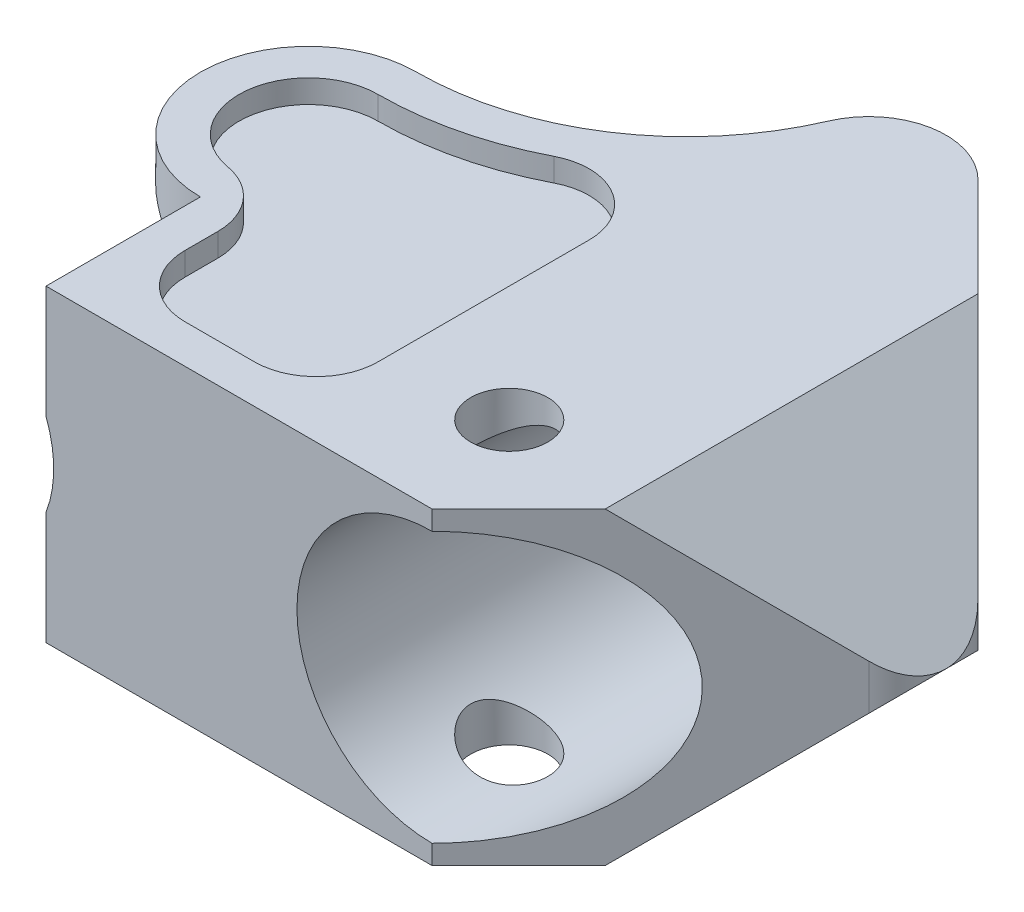
SolidWorks part; units mm, degrees
material "Alliage 1060"
ref_plane "Plan de face" through (0, 0, 0) normal (0, 0, 1) x (1, 0, 0)
ref_plane "Plan de dessus" through (0, 0, 0) normal (0, 1, 0) x (1, 0, 0)
ref_plane "Plan de droite" through (0, 0, 0) normal (1, 0, 0) x (0, 0, -1)
sketch "Esquisse1" plane through (0, 0, 0) normal (0, 1, 0) x (1, 0, 0)
  line L0 (0, 0) -> (50, 0)
  line L1 (50, 0) -> (78.2843, 28.2843)
  line L2 (0, 0) -> (0, 20)
  line L3 (78.2843, 42.4264) -> (48.4126, 72.2981)
  arc A0 (0, 20) -> (0, 48) centre (0, 34) cw
  arc A1 (0, 48) -> (32.1545, 69.1766) centre (0, 83) ccw
  arc A2 (78.2843, 28.2843) -> (78.2843, 42.4264) centre (71.2132, 35.3553) ccw
  arc A3 (48.4126, 72.2981) -> (32.1545, 69.1766) centre (41.3415, 65.227) ccw
  point P17 (85.3553, 35.3553)
  dimension "D5" = 14
  dimension "D7" = 70
  dimension "D8" = 10
  dimension "D3" = 135
  dimension "D4" = 20
  dimension "D6" = 90
  dimension "D1" = 50
  dimension "D2" = 50
extrude "Boss.-Extru.1" add sketch "Esquisse1" along normal mid plane 40
sketch "Esquisse2" plane through (0, 20, 0) normal (0, 1, 0) x (1, 0, 0)
  line L6 (30, 20) -> (30, 0)
  line L8 (30, 40.3385) -> (30, 13)
  line L9 (5, 26.5167) -> (5, 5)
  line L10 (5, 5) -> (47.9289, 5)
  line L11 (47.9289, 5) -> (74.7487, 31.8198)
  line L14 (74.7487, 38.8909) -> (44.8771, 68.7626)
  line L15 (5, 17.2668) -> (5, 13)
  line L16 (13, 5) -> (22, 5)
  arc A8 (5, 17.2668) -> (-1.5882, 25.1412) centre (-3, 17.2668) ccw
  arc A9 (5, 13) -> (13, 5) centre (13, 13) ccw
  arc A10 (22, 5) -> (30, 13) centre (22, 13) ccw
  arc A11 (30, 40.3385) -> (18.3333, 47.4488) centre (22, 40.3385) ccw
  arc A16 (74.7487, 31.8198) -> (74.7487, 38.8909) centre (71.2132, 35.3553) ccw
  arc A17 (44.8771, 68.7626) -> (36.748, 67.2018) centre (41.3415, 65.227) ccw
  arc A18 (0, 43) -> (36.748, 67.2018) centre (0, 83) ccw
  arc A19 (0, 43) -> (5, 26.5167) centre (0, 34) ccw
  arc A22 (0, 43) -> (18.3333, 47.4488) centre (0, 83) ccw
  arc A23 (0, 43) -> (-1.5882, 25.1412) centre (0, 34) ccw
  point P0 (30, 60.5211)
  dimension "D3" = 8
  dimension "D1" = 5
  dimension "D2" = 30
extrude "Enlèv. mat.-Extru.1" cut sketch "Esquisse2" against normal blind 3
sketch "Esquisse3" plane through (0, 0, 0) normal (0, 0, 1) x (1, 0, 0)
  line L0 (-14, 20) -> (-14, -20) construction
  line L1 (50, -20) -> (78.2843, -20) construction
  circle A0 centre (50, 0) radius 17.5
  circle A1 centre (-14, 0) radius 15
  dimension "D4" = 30
  dimension "D1" = 35
  dimension "D2" = 64
  dimension "D3" = 20
extrude "Enlèv. mat.-Extru.2" cut sketch "Esquisse3" against normal through all
sketch "Esquisse5" plane through (0, 20, 0) normal (0, 1, 0) x (1, 0, 0)
  line L0 (0, 20) -> (0, 0) construction
  line L1 (0, 0) -> (50, 0) construction
  circle A0 centre (45, 15) radius 5
  dimension "D1" = 10
  dimension "D2" = 45
  dimension "D3" = 15
extrude "Enlèv. mat.-Extru.3" cut sketch "Esquisse5" against normal through all
sketch "Esquisse6" plane through (0, 0, 0) normal (0, 0, 1) x (1, 0, 0)
  line L0 (81.2132, 20) -> (61.2132, 20)
  line L1 (50, 20) -> (78.2843, 20) construction
  line L2 (61.2132, 20) -> (81.2132, 0)
  line L3 (81.2132, -20) -> (81.2132, 20) construction
  line L9 (81.2132, 0) -> (101.5623, 0) construction
  line L12 (81.2132, -20) -> (81.2132, 20)
  line L13 (61.2132, -20) -> (81.2132, 0)
  line L14 (81.2132, -20) -> (61.2132, -20)
  dimension "D2" = 20
  dimension "D3" = 20
extrude "Enlèv. mat.-Extru.4" cut sketch "Esquisse6" against normal through all contours L2 L12 L0 | L14 L12 L13
equation "\"A\"= 50"
equation "\"B\"= 15"
equation "\"C\"= \"B\" + 20"
equation "\"D4@Esquisse3\"=\"B\" * 2"
equation "\"D1@Esquisse1\"=\"A\""
equation "\"D1@Esquisse3\"=\"C\""
equation "\"D2@Esquisse1\"=\"A\""
